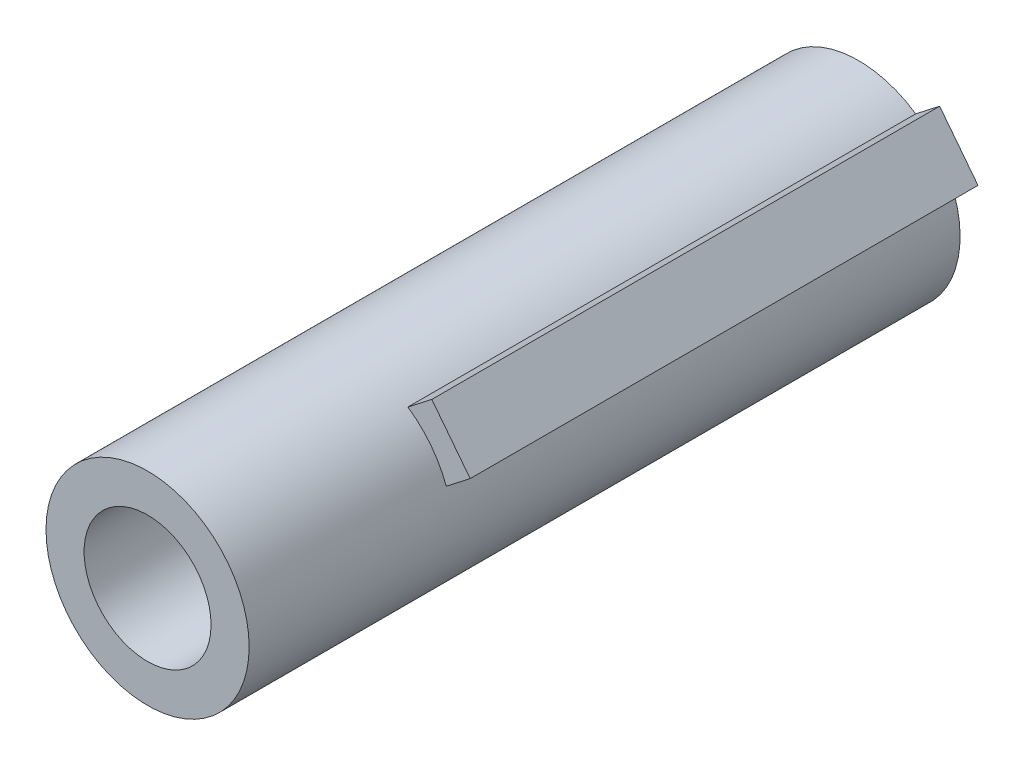
SolidWorks part; units mm, degrees
ref_plane "前视基准面" through (0, 0, 0) normal (0, 0, 1) x (1, 0, 0)
ref_plane "上视基准面" through (0, 0, 0) normal (0, 1, 0) x (1, 0, 0)
ref_plane "右视基准面" through (0, 0, 0) normal (1, 0, 0) x (0, 0, -1)
sketch "草图1" plane through (0, 0, 0) normal (0, 0, 1) x (1, 0, 0)
  line L1 (3.1954, 4.0381) -> (2.2518, 3.306)
  line L2 (3.1954, 4.0381) -> (4.7054, 2.0919)
  line L3 (4.7054, 2.0919) -> (3.7618, 1.3598)
  arc A0 (2.2518, 3.306) -> (3.7618, 1.3598) centre (0, 0) ccw
  dimension "D1" = 5
  dimension "D2" = 4
extrude "凸台-拉伸1" add sketch "草图1" along normal blind 20
sketch "草图2" plane through (0, 0, 20) normal (0, 0, 1) x (1, 0, 0)
  circle A0 centre (0, 0) radius 4
extrude "凸台-拉伸2" add sketch "草图2" along normal blind 8
sketch "草图3" plane through (0, 0, 28) normal (0, 0, 1) x (1, 0, 0)
  circle A0 centre (0, 0) radius 2.5
extrude "切除-拉伸1" cut sketch "草图3" against normal blind 20 contours A0
